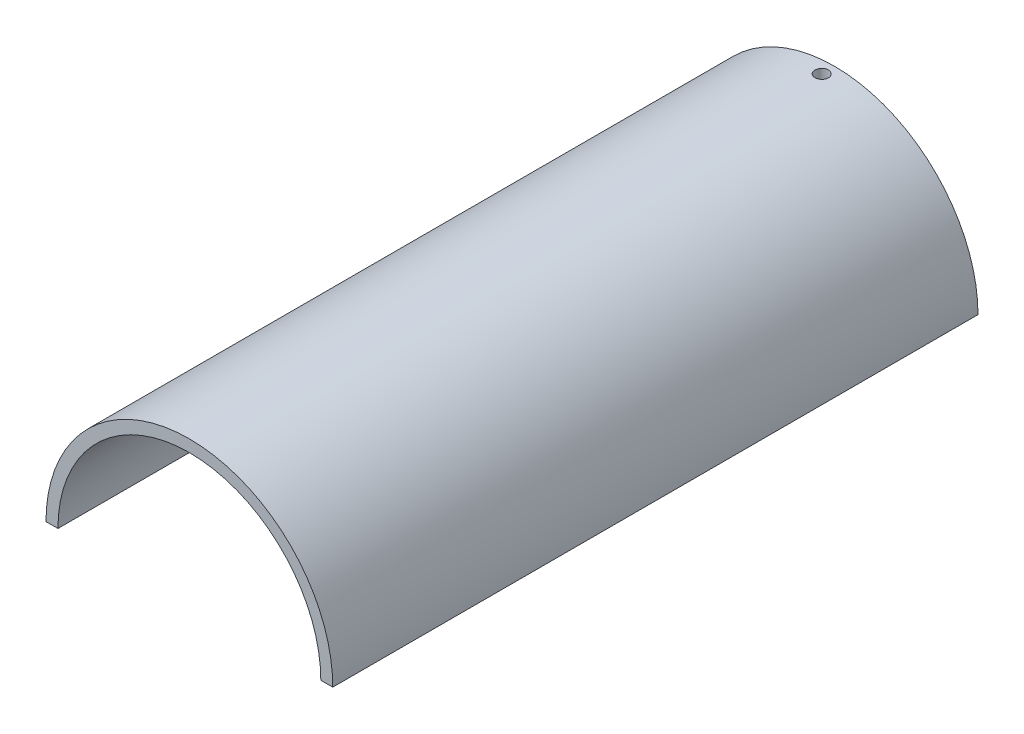
SolidWorks part; units mm, degrees
ref_plane "Front Plane" through (0, 0, 0) normal (0, 0, 1) x (1, 0, 0)
ref_plane "Top Plane" through (0, 0, 0) normal (0, 1, 0) x (1, 0, 0)
ref_plane "Right Plane" through (0, 0, 0) normal (1, 0, 0) x (0, 0, -1)
sketch "Sketch1" plane through (0, 0, 0) normal (0, 0, 1) x (1, 0, 0)
  line L0 (-38.1, 0) -> (38.1, 0) construction
  line L1 (-38.1, 0) -> (-34.925, 0)
  line L2 (34.925, 0) -> (38.1, 0)
  arc A0 (38.1, 0) -> (-38.1, 0) centre (0, 0) ccw
  arc A1 (34.925, 0) -> (-34.925, 0) centre (0, 0) ccw
  dimension "D1" = 3.175
extrude "Boss-Extrude1" add sketch "Sketch1" along normal blind 171.45
ref_plane "Plane1" through (0, 38.1, 0) normal (0, 1, 0) x (1, 0, 0)
hole_wizard "9/64 (0.14063) Diameter Hole1" positions "Sketch3" profile "Sketch2" hole size "9/64" standard "ANSI Inch" end condition through all
sketch "Sketch3" plane through (0, 38.1, 0) normal (0, 1, 0) x (1, 0, 0)
  point P0 (0, -3.4468)
  dimension "D1" = 3.4468
sketch "Sketch2" plane through (0, 38.1, 3.4468) normal (1, 0, 0) x (0, 0, 1)
  line L0 (0, 0) -> (0, 38.1)
  line L1 (0, 38.1) -> (1.786, 38.1)
  line L2 (1.786, 38.1) -> (1.786, 0)
  line L5 (1.786, 0) -> (0, 0)
  line L11 (0, -6.35) -> (0, 107.95) construction
  dimension "Thru Hole Dia." = 3.572
  dimension "Thru Hole Depth" = 38.1
